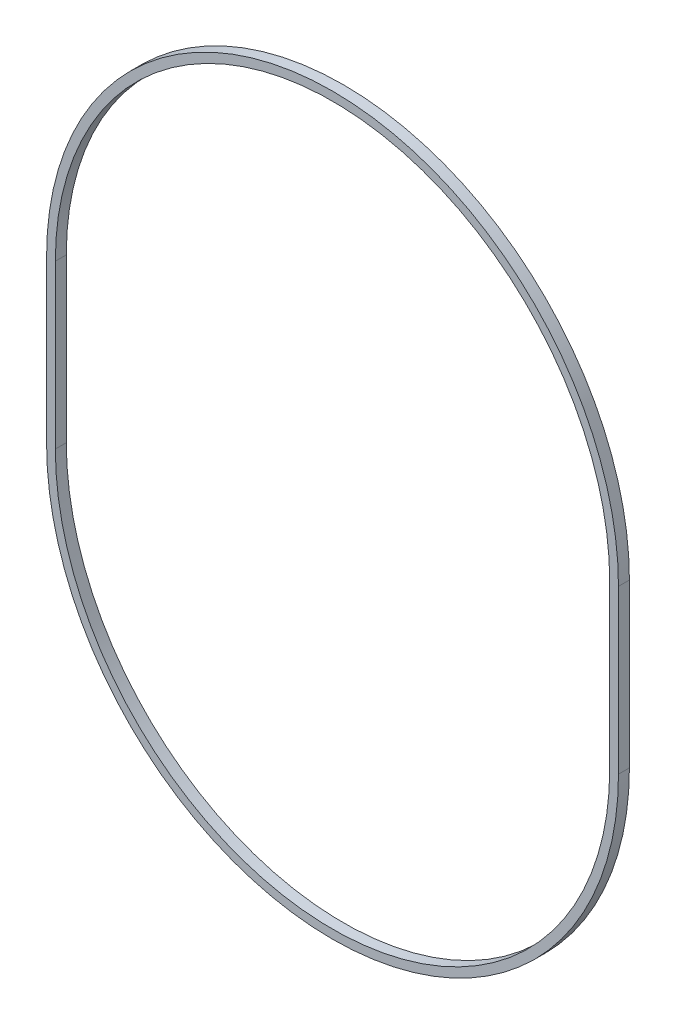
SolidWorks part; units mm, degrees
material "AISI 304"
ref_plane "Front Plane" through (0, 0, 0) normal (0, 0, 1) x (1, 0, 0)
ref_plane "Top Plane" through (0, 0, 0) normal (0, 1, 0) x (1, 0, 0)
ref_plane "Right Plane" through (0, 0, 0) normal (1, 0, 0) x (0, 0, -1)
sketch "Sketch1" plane through (0, 0, 0) normal (0, 0, 1) x (1, 0, 0)
  line B0 (-127.19, 27.875) -> (-127.19, -27.875)
  line B1 (127.19, -27.875) -> (127.19, 27.875)
  line B2 (-98, 27.875) -> (-98, -27.875)
  line B3 (98, -27.875) -> (98, 27.875)
  line B4 (95, -27.875) -> (95, 27.875)
  line B5 (-95, 27.875) -> (-95, -27.875)
  line B6 (124.19, -27.875) -> (124.19, 27.875)
  line B7 (-124.19, 27.875) -> (-124.19, -27.875)
  line B8 (-95, 27.875) -> (-95, -27.875)
  line B9 (95, -27.875) -> (95, 27.875)
  arc B10 (127.19, 27.875) -> (-127.19, 27.875) centre (0, 27.875) ccw
  arc B11 (-127.19, -27.875) -> (127.19, -27.875) centre (0, -27.875) ccw
  arc B12 (98, 27.875) -> (-98, 27.875) centre (0, 27.875) ccw
  arc B13 (-98, -27.875) -> (98, -27.875) centre (0, -27.875) ccw
  arc B14 (95, 27.875) -> (-95, 27.875) centre (0, 27.875) ccw
  arc B15 (-95, -27.875) -> (95, -27.875) centre (0, -27.875) ccw
  arc B16 (-124.19, -27.875) -> (124.19, -27.875) centre (0, -27.875) ccw
  arc B17 (-95, -27.875) -> (95, -27.875) centre (0, -27.875) ccw
  arc B18 (124.19, 27.875) -> (-124.19, 27.875) centre (0, 27.875) ccw
  arc B19 (98, 27.875) -> (-98, 27.875) centre (0, 27.875) ccw
  arc B20 (95, 27.875) -> (-95, 27.875) centre (0, 27.875) ccw
sketch_block_instance "GasketRim-1"
sketch_block "GasketRim"
extrude "Boss-Extrude1" add sketch "Sketch1" along normal mid plane 3.75 contours B2 B13 B3 B12 B15 B5 B14 B4
